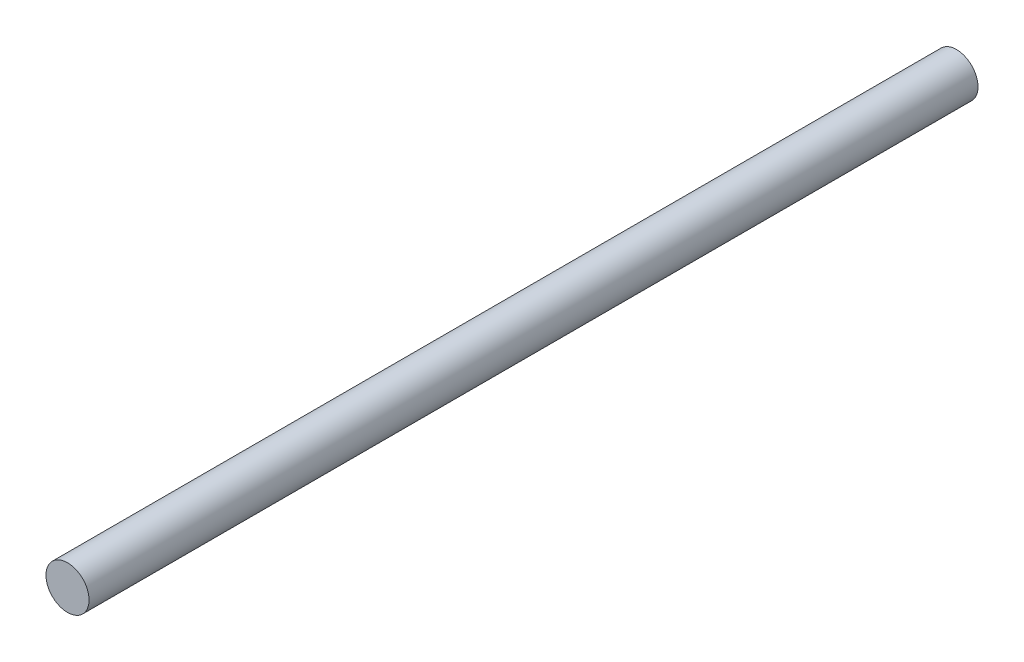
SolidWorks part; units mm, degrees
ref_plane "Alzado" through (0, 0, 0) normal (0, 0, 1) x (1, 0, 0)
ref_plane "Planta" through (0, 0, 0) normal (0, 1, 0) x (1, 0, 0)
ref_plane "Vista lateral" through (0, 0, 0) normal (1, 0, 0) x (0, 0, -1)
sketch "Croquis1" plane through (0, 0, 0) normal (0, 0, 1) x (1, 0, 0)
  circle A0 centre (0, 0) radius 4
extrude "Saliente-Extruir1" add sketch "Croquis1" along normal blind 165
